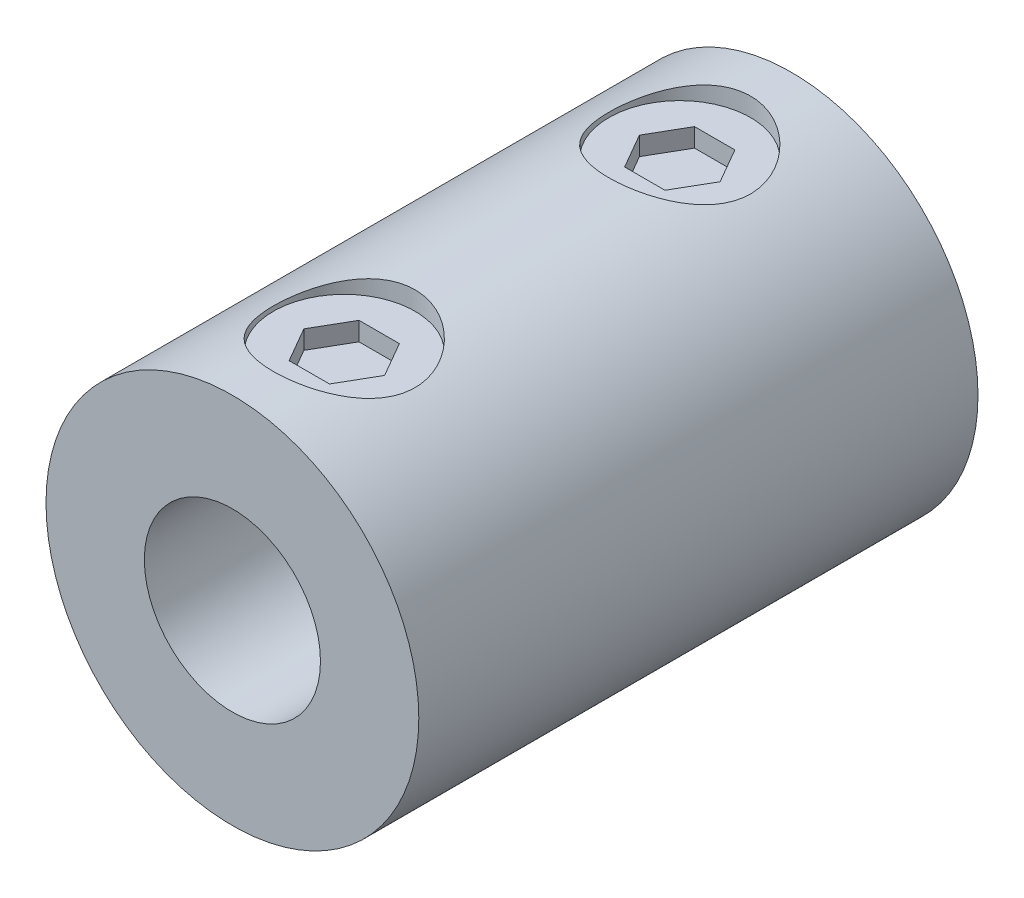
SolidWorks part; units mm, degrees
material "AISI 304"
ref_plane "Frontal Plane" through (0, 0, 0) normal (0, 0, 1) x (1, 0, 0)
ref_plane "Horizontal Plane" through (0, 0, 0) normal (0, 1, 0) x (1, 0, 0)
ref_plane "Profile Plane" through (0, 0, 0) normal (1, 0, 0) x (0, 0, -1)
sketch "Sketch2" plane through (0, 0, 0) normal (1, 0, 0) x (0, 0, -1)
  line L0 (0, 0) -> (19.05, 0) construction
  line L1 (0, 3) -> (0, 6.35)
  line L2 (0, 6.35) -> (19.05, 6.35)
  line L3 (19.05, 6.35) -> (19.05, 3.9688)
  line L4 (19.05, 3.9688) -> (9.525, 3.9687)
  line L5 (9.525, 3.9687) -> (9.525, 3)
  line L6 (9.525, 3) -> (0, 3)
  point P14 (9.525, 6.35)
  dimension "D1" = 6.35
  dimension "D2" = 19.05
  dimension "D3" = 3
  dimension "D4" = 3.9688
revolve "Revolve1" add sketch "Sketch2" angle 360 about L0
ref_plane "Plane1" through (0, 6.35, 0) normal (0, 1, 0) x (1, 0, 0)
sketch "Sketch4" plane through (0, 6.35, 0) normal (0, 1, 0) x (1, 0, 0)
  circle A0 centre (0, 3.81) radius 2.413
  dimension "D1" = 4.826
  dimension "D2" = 3.81
extrude "Cut-Extrude1" cut sketch "Sketch4" against normal blind 1.27
sketch "Sketch3" plane through (0, 5.08, 0) normal (0, 1, 0) x (1, 0, 0)
  line L0 (-6.35, 0) -> (6.35, 0) construction
  line L3 (1.3748, 3.81) -> (0.6874, 5.0006)
  line L4 (0.6874, 5.0006) -> (-0.6874, 5.0006)
  line L5 (-0.6874, 5.0006) -> (-1.3748, 3.81)
  line L6 (-1.3748, 3.81) -> (-0.6874, 2.6194)
  line L7 (-0.6874, 2.6194) -> (0.6874, 2.6194)
  line L8 (0.6874, 2.6194) -> (1.3748, 3.81)
  circle A1 centre (0, 3.81) radius 2.413
  circle A2 centre (0, 3.81) radius 1.1906 construction
  dimension "D1" = 4.826
  dimension "D2" = 3.81
  dimension "D4" = 2.3813
extrude "Boss-Extrude1" add sketch "Sketch3" along normal blind 0.635
ref_plane "Plane2" through (0, 0, -9.525) normal (0, 0, 1) x (1, 0, 0)
mirror "Mirror1" about plane through (0, 0, -9.525) normal (0, 0, 1) of "Boss-Extrude1", "Cut-Extrude1"
